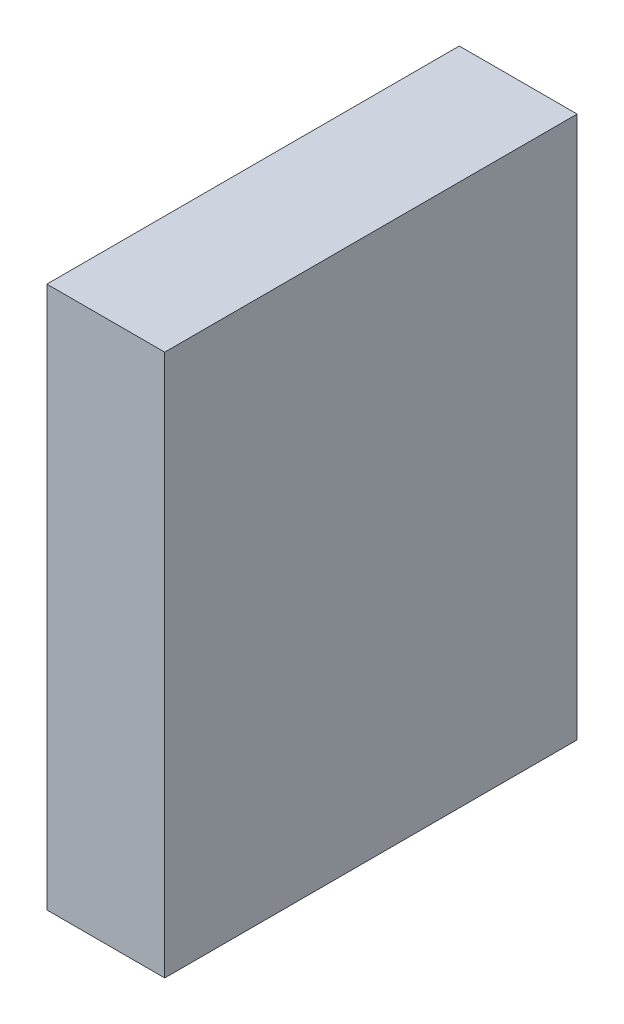
SolidWorks part; units mm, degrees
ref_plane "Ground" through (0, 0, 0) normal (0, 0, 1) x (1, 0, 0)
ref_plane "Right" through (0, 0, 0) normal (0, 1, 0) x (1, 0, 0)
ref_plane "Front" through (0, 0, 0) normal (1, 0, 0) x (0, 0, -1)
sketch "Sketch1" plane through (0, 0, 0) normal (1, 0, 0) x (0, 0, -1)
  line L1 (17.5, -23) -> (-17.5, -23)
  line L2 (17.5, -23) -> (17.5, 23)
  line L3 (17.5, 23) -> (-17.5, 23)
  line L4 (-17.5, -23) -> (-17.5, 23)
  line L5 (17.5, -23) -> (-17.5, 23) construction
  line L6 (17.5, 23) -> (-17.5, -23) construction
  point P0 (0, 0)
  dimension "D1" = 46
  dimension "D2" = 35
extrude "Boss-Extrude1" add sketch "Sketch1" along normal blind 10
